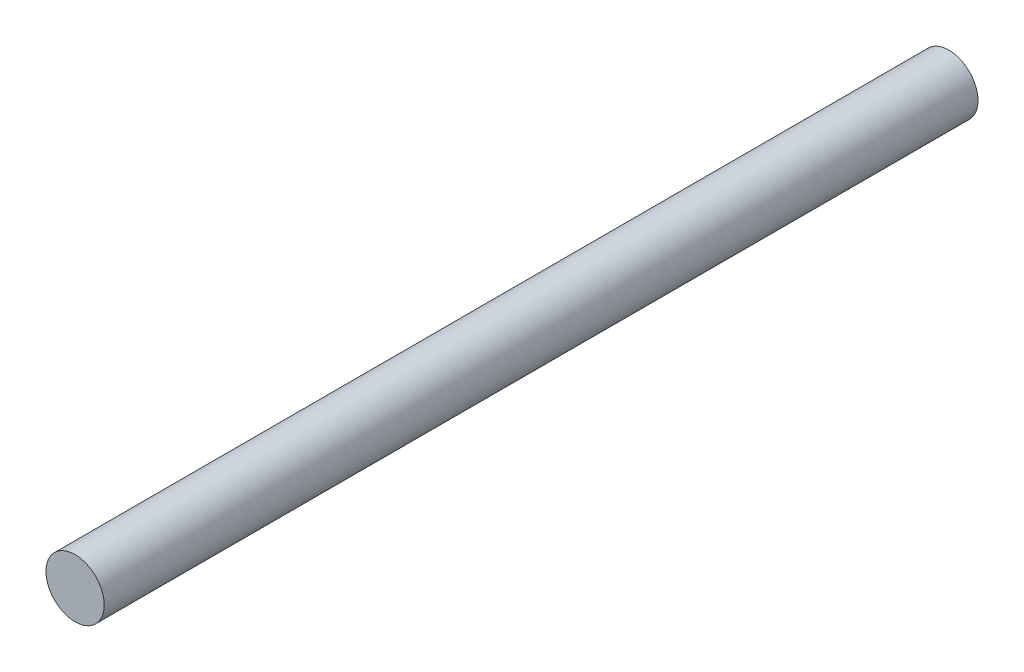
SolidWorks part; units mm, degrees
ref_plane "Alzado" through (0, 0, 0) normal (0, 0, 1) x (1, 0, 0)
ref_plane "Planta" through (0, 0, 0) normal (0, 1, 0) x (1, 0, 0)
ref_plane "Vista lateral" through (0, 0, 0) normal (1, 0, 0) x (0, 0, -1)
sketch "Croquis1" plane through (0, 0, 0) normal (0, 0, 1) x (1, 0, 0)
  circle A0 centre (0, 0) radius 5
  dimension "D1" = 10
extrude "Saliente-Extruir1" add sketch "Croquis1" along normal blind 150
